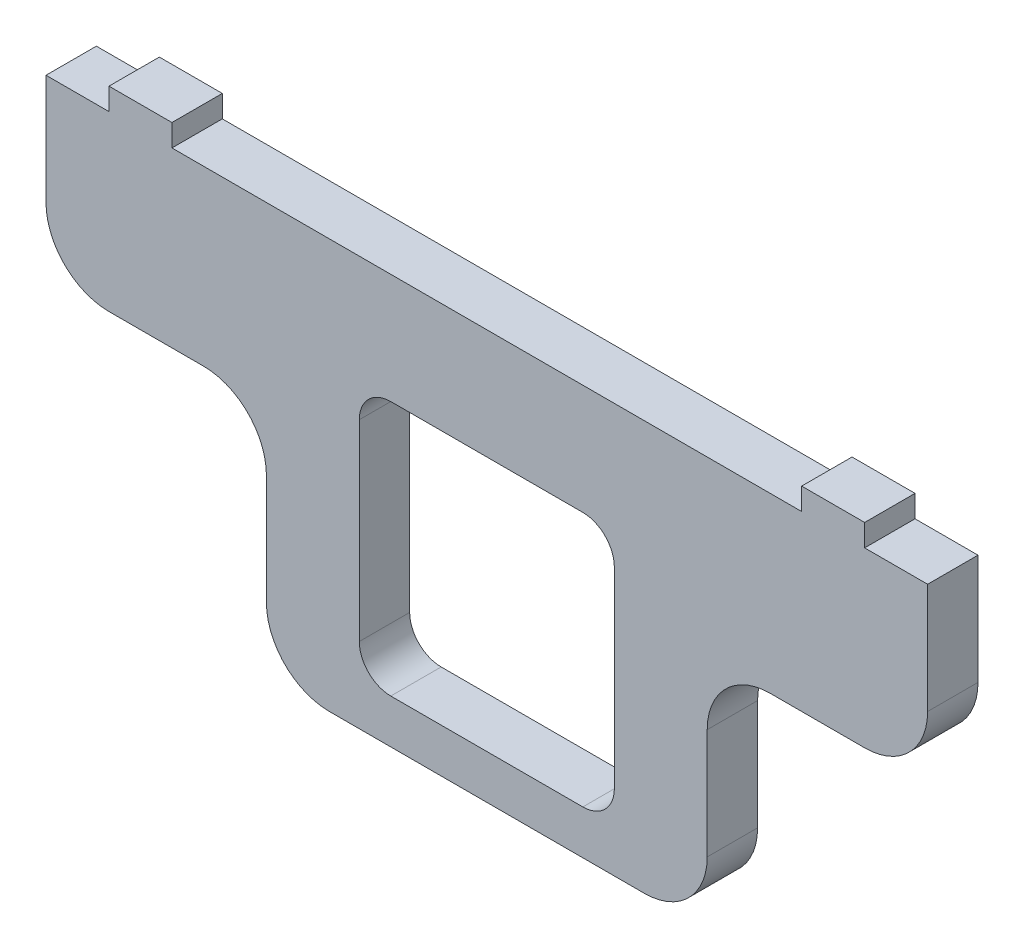
SolidWorks part; units mm, degrees
material "Q355"
ref_plane "前视基准面" through (0, 0, 0) normal (0, 0, 1) x (1, 0, 0)
ref_plane "上视基准面" through (0, 0, 0) normal (0, 1, 0) x (1, 0, 0)
ref_plane "右视基准面" through (0, 0, 0) normal (1, 0, 0) x (0, 0, -1)
sketch "草图1" plane through (0, 0, 0) normal (0, 0, 1) x (1, 0, 0)
  line L0 (0, 0) -> (0, 168.111) construction
  line L1 (-70, 0) -> (70, 0)
  line L2 (70, 0) -> (70, 75)
  line L3 (70, 75) -> (140, 75)
  line L4 (140, 75) -> (140, 130)
  line L5 (140, 130) -> (120, 130)
  line L6 (120, 130) -> (120, 137)
  line L7 (120, 137) -> (100, 137)
  line L8 (100, 137) -> (100, 130)
  line L9 (100, 130) -> (-100, 130)
  line L10 (-40.5, 95) -> (40.5, 95)
  line L11 (40.5, 95) -> (40.5, 14)
  line L12 (40.5, 14) -> (-40.5, 14)
  line L13 (-40.5, 95) -> (-40.5, 14)
  line L14 (-100, 137) -> (-100, 130)
  line L15 (-120, 137) -> (-100, 137)
  line L16 (-120, 130) -> (-120, 137)
  line L17 (-140, 130) -> (-120, 130)
  line L18 (-140, 75) -> (-140, 130)
  line L19 (-70, 75) -> (-140, 75)
  line L20 (-70, 0) -> (-70, 75)
  point P17 (0, 14)
  point P18 (0, 95)
  point P19 (0, 130)
  dimension "D1" = 140
  dimension "D2" = 75
  dimension "D3" = 130
  dimension "D4" = 280
  dimension "D5" = 200
  dimension "D6" = 20
  dimension "D7" = 7
  dimension "D8" = 14
  dimension "D9" = 81
  dimension "D10" = 81
extrude "凸台-拉伸1" add sketch "草图1" along normal mid plane 16
fillet "圆角1" radius 20 6 edges at (70, 75, 0) (-70, 75, 0) (70, 0, 0) (-70, 0, 0) (140, 75, 0) (-140, 75, 0)
fillet "圆角2" radius 10 4 edges at (40.5, 14, 0) (-40.5, 14, 0) (40.5, 95, 0) (-40.5, 95, 0)
